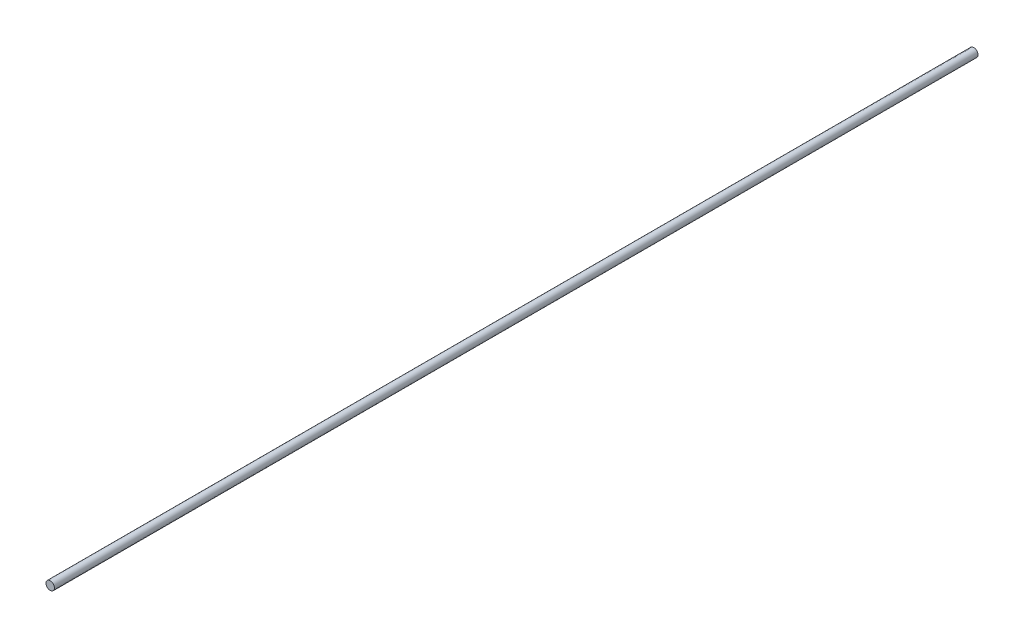
SolidWorks part; units mm, degrees
ref_plane "Front Plane" through (0, 0, 0) normal (0, 0, 1) x (1, 0, 0)
ref_plane "Top Plane" through (0, 0, 0) normal (0, 1, 0) x (1, 0, 0)
ref_plane "Right Plane" through (0, 0, 0) normal (1, 0, 0) x (0, 0, -1)
sketch "Sketch1" plane through (0, 0, 0) normal (0, 0, 1) x (1, 0, 0)
  circle A0 centre (0, 0) radius 4
extrude "Boss-Extrude1" add sketch "Sketch1" along normal blind 875
